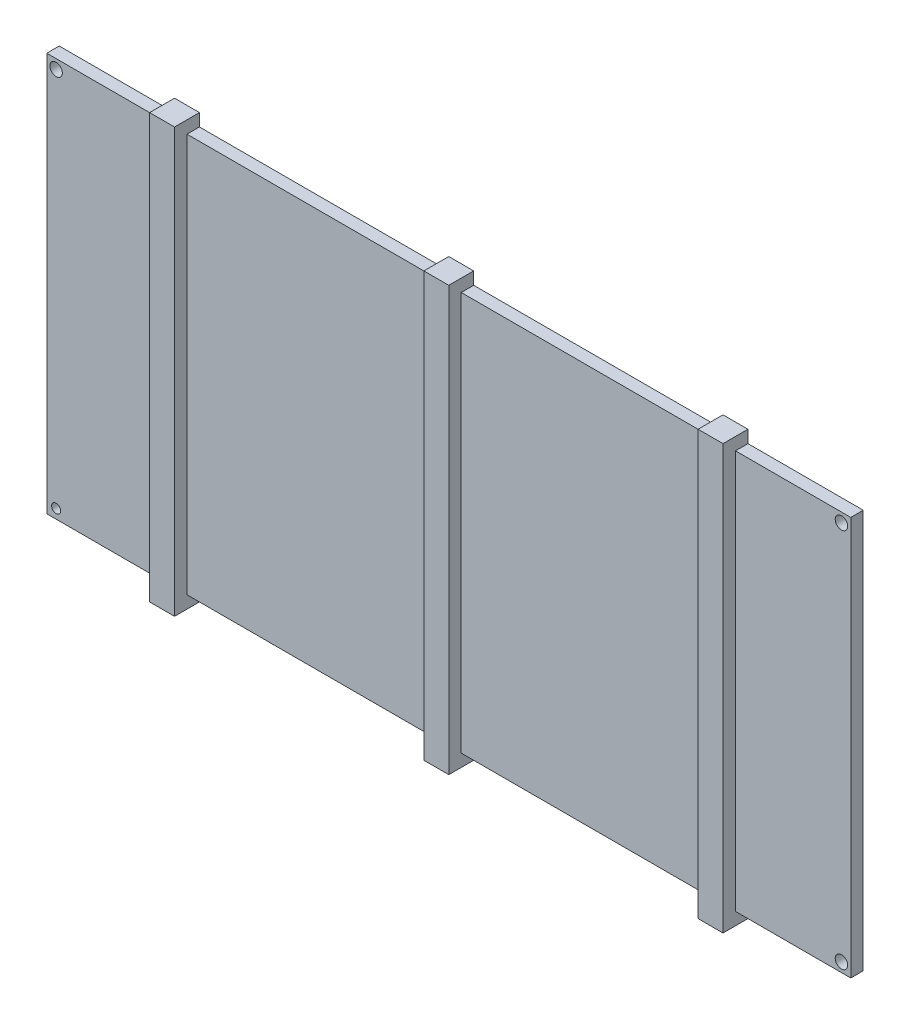
SolidWorks part; units mm, degrees
ref_plane "前视基准面" through (0, 0, 0) normal (0, 0, 1) x (1, 0, 0)
ref_plane "上视基准面" through (0, 0, 0) normal (0, 1, 0) x (1, 0, 0)
ref_plane "右视基准面" through (0, 0, 0) normal (1, 0, 0) x (0, 0, -1)
sketch "Model" plane through (0, 0, 0) normal (0, 0, 1) x (1, 0, 0)
  line L0 (257.5557, 185.1803) -> (276.0557, 185.1803)
  line L1 (386.5557, 121.1803) -> (368.0557, 121.1803)
  line L2 (257.5557, 121.1803) -> (257.5557, 133.1803)
  line L3 (386.5557, 185.1803) -> (386.5557, 173.1803)
  line L4 (324.0557, 185.1803) -> (324.0557, 187.1803)
  line L5 (324.0557, 187.1803) -> (320.0557, 187.1803)
  line L6 (320.0557, 187.1803) -> (320.0557, 185.1803)
  line L7 (280.0557, 185.1803) -> (280.0557, 187.1803)
  line L8 (280.0557, 187.1803) -> (276.0557, 187.1803)
  line L9 (276.0557, 187.1803) -> (276.0557, 185.1803)
  line L10 (368.0557, 185.1803) -> (368.0557, 187.1803)
  line L11 (368.0557, 187.1803) -> (364.0557, 187.1803)
  line L12 (364.0557, 187.1803) -> (364.0557, 185.1803)
  line L13 (280.0557, 121.1803) -> (280.0557, 119.1803)
  line L14 (280.0557, 119.1803) -> (276.0557, 119.1803)
  line L15 (276.0557, 119.1803) -> (276.0557, 121.1803)
  line L16 (368.0557, 121.1803) -> (368.0557, 119.1803)
  line L17 (368.0557, 119.1803) -> (364.0557, 119.1803)
  line L18 (364.0557, 119.1803) -> (364.0557, 121.1803)
  line L19 (386.5557, 173.1803) -> (386.5557, 169.1803)
  line L20 (386.5557, 137.1803) -> (386.5557, 133.1803)
  line L21 (257.5557, 137.1803) -> (257.5557, 133.1803)
  line L22 (257.5557, 173.1803) -> (257.5557, 169.1803)
  line L23 (324.0557, 121.1803) -> (332.5557, 121.1803)
  line L24 (322.0557, 119.1803) -> (324.0557, 119.1803)
  line L25 (324.0557, 119.1803) -> (324.0557, 121.1803)
  line L26 (322.0557, 119.1803) -> (320.0557, 119.1803)
  line L27 (320.0557, 119.1803) -> (320.0557, 121.1803)
  line L31 (257.5557, 173.1803) -> (257.5557, 185.1803)
  line L32 (257.5557, 137.1803) -> (257.5557, 169.1803)
  line L33 (276.0557, 121.1803) -> (257.5557, 121.1803)
  line L34 (364.0557, 121.1803) -> (332.5557, 121.1803)
  line L35 (386.5557, 133.1803) -> (386.5557, 121.1803)
  line L36 (386.5557, 169.1803) -> (386.5557, 137.1803)
  line L37 (368.0557, 185.1803) -> (386.5557, 185.1803)
  line L38 (311.5557, 121.1803) -> (320.0557, 121.1803)
  line L41 (311.5557, 121.1803) -> (280.0557, 121.1803)
  line L42 (280.0557, 185.1803) -> (320.0557, 185.1803)
  line L43 (324.0557, 185.1803) -> (364.0557, 185.1803)
  point P2 (0, 0)
extrude "凸台-拉伸1" add sketch "Model" along normal blind 2
sketch "草图2" plane through (0, 0, 2) normal (0, 0, 1) x (1, 0, 0)
  line L0 (364.0557, 119.1803) -> (368.0557, 119.1803) construction
  line L1 (368.0557, 187.1803) -> (364.0557, 187.1803) construction
  line L2 (320.0557, 119.1803) -> (324.0557, 119.1803) construction
  line L3 (324.0557, 187.1803) -> (320.0557, 187.1803) construction
  line L4 (276.0557, 119.1803) -> (280.0557, 119.1803) construction
  line L5 (280.0557, 187.1803) -> (276.0557, 187.1803) construction
  line L6 (364.0557, 119.1803) -> (368.0557, 119.1803)
  line L7 (368.0557, 187.1803) -> (364.0557, 187.1803)
  line L8 (320.0557, 119.1803) -> (324.0557, 119.1803)
  line L9 (324.0557, 187.1803) -> (320.0557, 187.1803)
  line L10 (276.0557, 119.1803) -> (280.0557, 119.1803)
  line L11 (280.0557, 187.1803) -> (276.0557, 187.1803)
  line L12 (276.0557, 187.1803) -> (276.0557, 119.1803)
  line L13 (280.0557, 187.1803) -> (280.0557, 119.1803)
  line L14 (320.0557, 187.1803) -> (320.0557, 119.1803)
  line L15 (324.0557, 187.1803) -> (324.0557, 119.1803)
  line L16 (364.0557, 187.1803) -> (364.0557, 119.1803)
  line L17 (368.0557, 187.1803) -> (368.0557, 119.1803)
extrude "凸台-拉伸2" add sketch "草图2" along normal blind 2
sketch "草图3" plane through (0, 0, 2) normal (0, 0, 1) x (1, 0, 0)
  line L0 (257.5557, 185.1803) -> (257.5557, 121.1803) construction
  line L1 (276.0557, 185.1803) -> (257.5557, 185.1803) construction
  line L2 (386.5557, 185.1803) -> (368.0557, 185.1803) construction
  line L3 (386.5557, 121.1803) -> (386.5557, 185.1803) construction
  line L4 (368.0557, 121.1803) -> (386.5557, 121.1803) construction
  circle A0 centre (259.0557, 183.6803) radius 1
  circle A1 centre (385.0557, 183.6803) radius 1
  circle A2 centre (385.0557, 122.6803) radius 1
  circle A3 centre (259.0557, 122.6803) radius 0.725
  dimension "D1" = 2
  dimension "D4" = 2
  dimension "D5" = 1.5
  dimension "D7" = 2
  dimension "D9" = 1.45
  dimension "D2" = 1.5
  dimension "D3" = 1.5
  dimension "D6" = 1.5
  dimension "D8" = 1.5
extrude "切除-拉伸1" cut sketch "草图3" against normal blind 5
